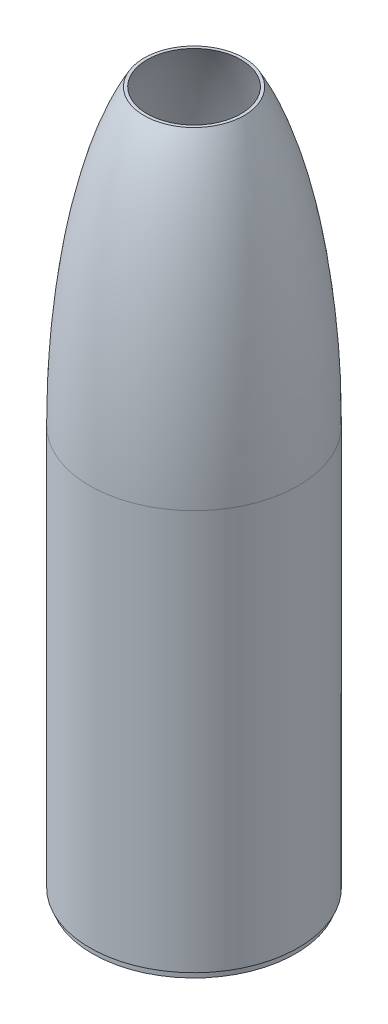
SolidWorks part; units mm, degrees
ref_plane "Front Plane" through (0, 0, 0) normal (0, 0, 1) x (1, 0, 0)
ref_plane "Top Plane" through (0, 0, 0) normal (0, 1, 0) x (1, 0, 0)
ref_plane "Right Plane" through (0, 0, 0) normal (1, 0, 0) x (0, 0, -1)
sketch "Sketch1" plane through (0, 0, 0) normal (0, 0, 1) x (1, 0, 0)
  line L9 (0, 0) -> (0, 654.6147) construction
  line L12 (76.2, 300) -> (76.2, 0)
  line L13 (78.16, 300) -> (78.16, 0)
  line L14 (0, 550) -> (0, 548.04)
  line L15 (76.2, 0) -> (78.16, 0)
  ellipse E0 centre (0, 300) end of major axis (0, 51.96) minor radius 76.2 (0, 548.04) -> (76.2, 300) cw
  spline S0 degree 1 poles (0, 550) (78.16, 300) knots 0 0 1 1 construction
  spline S1 degree 3 poles (0, 550) (2.7231, 550) (8.0954, 549.1311) (15.9852, 545.3134) (23.5507, 539.1306) (33.2071, 527.8754) (44.4036, 508.3688) (56.1093, 477.0871) (65.6898, 439.0807) (71.6144, 402.9938) (74.988, 372.2996) (76.8127, 348.5857) (77.9144, 324.416) (78.16, 308.1247) (78.16, 300) knots -1.570796 -1.570796 -1.570796 -1.570796 -1.472622 -1.374447 -1.276272 -1.178097 -0.981748 -0.785398 -0.589049 -0.392699 -0.294524 -0.19635 -0.098175 0 0 0 0
  point P7 (140, 150)
  point P8 (-133.3333, 150)
  point P9 (-4.7059, 391.1765)
  dimension "D4" = 76.2
  dimension "D2" = 300
  dimension "D3" = 76.2
  dimension "D5" = 1.96
revolve "Revolve1" add sketch "Sketch1" angle 360 about L9
ref_plane "Plane1" through (0, 300, 0) normal (0, 1, 0) x (1, 0, 0)
sketch "Sketch2" plane through (0, 300, 0) normal (0, 1, 0) x (1, 0, 0)
  circle A0 centre (0, 0) radius 76.2 construction
  circle A1 centre (0, 0) radius 76.2
  circle A2 centre (0, 0) radius 74.2
  dimension "D1" = 2
extrude "Boss-Extrude1" add sketch "Sketch2" against normal blind 304.8
ref_plane "Plane2" through (0, 550, 0) normal (0, -1, 0) x (-1, 0, 0)
sketch "Sketch3" plane through (0, 550, 0) normal (0, -1, 0) x (-1, 0, 0)
  circle A0 centre (0, 0) radius 102.134
extrude "Cut-Extrude1" cut sketch "Sketch3" along normal blind 30 contours A0
